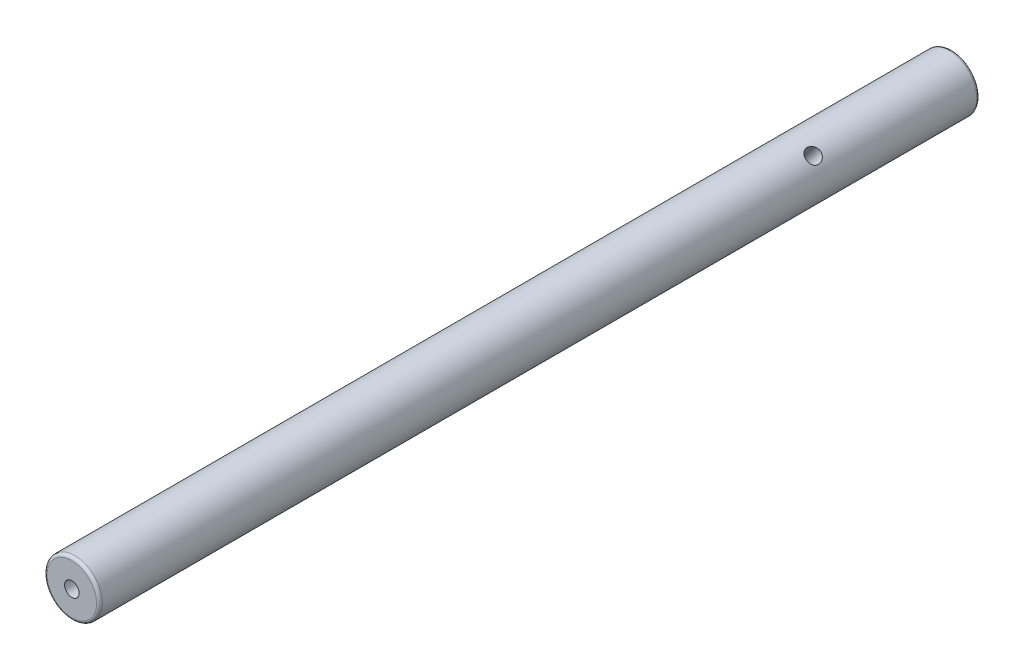
SolidWorks part; units mm, degrees
ref_plane "Plano frontal" through (0, 0, 0) normal (0, 0, 1) x (1, 0, 0)
ref_plane "Plano superior" through (0, 0, 0) normal (0, 1, 0) x (1, 0, 0)
ref_plane "Plano direito" through (0, 0, 0) normal (1, 0, 0) x (0, 0, -1)
sketch "Esboço1" plane through (0, 0, 0) normal (0, 0, 1) x (1, 0, 0)
  circle A0 centre (21.9, 0.4624) radius 4.7625
  dimension "D1" = 9.525
extrude "Ressalto-extrusão1" add sketch "Esboço1" along normal blind 151.9
hole_wizard "Furo roscado de M5x0.81" positions "Esboço3" profile "Esboço2" tap size "M5x0.8" standard "Métrico Ansi"
sketch "Esboço3" plane through (0, 0, 0) normal (0, 0, -1) x (-1, 0, 0)
  point P0 (-21.9, 0.4624)
sketch "Esboço2" plane through (21.9, 0.4624, 0) normal (1, 0, 0) x (0, 1, 0)
  line L0 (0, 0) -> (0, 15.2618)
  line L1 (0, 15.2618) -> (2.1, 14)
  line L2 (2.1, 14) -> (2.1, 0)
  line L5 (2.1, 0) -> (0, 0)
  line L10 (0, 15.2618) -> (-2.1, 14) construction
  line L11 (0, -6.35) -> (0, 107.95) construction
  dimension "Tap Drill Dia." = 4.2
  dimension "Tap Drill Depth" = 14
  dimension "Drill Angle" = 118
cosmetic thread "Rosca de furo1" parameters "D1"=10, "D2"=5
cosmetic thread "Representação de rosca2" parameters "D1"=5, "D2"=5
fillet "Filete1" radius 0.5 1 edges at (26.6625, 0.4624, 0)
hole_wizard "Broca de rosquear para tarraxa de M3x0.51" positions "Esboço9" profile "Esboço8" hole size "M3x0.5" standard "Métrico Ansi"
sketch "Esboço9" plane through (0, 0, 151.9) normal (0, 0, 1) x (1, 0, 0)
  circle A0 centre (21.9, 0.4624) radius 4.7625 construction
  point P0 (21.9, 0.4624)
  dimension "D1" = 0
sketch "Esboço8" plane through (21.9, 0.4624, 151.9) normal (1, 0, 0) x (0, -1, 0)
  line L0 (0, 0) -> (0, 5.7511)
  line L1 (0, 5.7511) -> (1.25, 5)
  line L2 (1.25, 5) -> (1.25, 0)
  line L5 (1.25, 0) -> (0, 0)
  line L10 (0, 5.7511) -> (-1.25, 5) construction
  line L11 (0, -6.35) -> (0, 107.95) construction
  dimension "Hole Dia." = 2.5
  dimension "Hole Depth" = 5
  dimension "Drill Angle" = 118
fillet "Filete2" radius 0.5 1 edges at (26.6625, 0.4624, 151.9)
hole_wizard "Broca de rosquear para tarraxa de M3x0.52" positions "3DSketch1" profile "Esboço10" hole size "M3x0.5" standard "Métrico Ansi"
sketch3d "3DSketch1"
  point P0 (18.9703, -3.2924, 26.8798)
sketch "Esboço10" plane through (18.9703, -3.2924, 26.8798) normal (0, 0, 1) x (0.7884, -0.6152, 0)
  line L0 (0, 0) -> (0, 10.7511)
  line L1 (0, 10.7511) -> (1.25, 10)
  line L2 (1.25, 10) -> (1.25, 0)
  line L5 (1.25, 0) -> (0, 0)
  line L10 (0, 10.7511) -> (-1.25, 10) construction
  line L11 (0, -6.35) -> (0, 107.95) construction
  dimension "Hole Dia." = 2.5
  dimension "Hole Depth" = 10
  dimension "Drill Angle" = 118
cosmetic thread "Representação de rosca1" parameters "D2"=3
